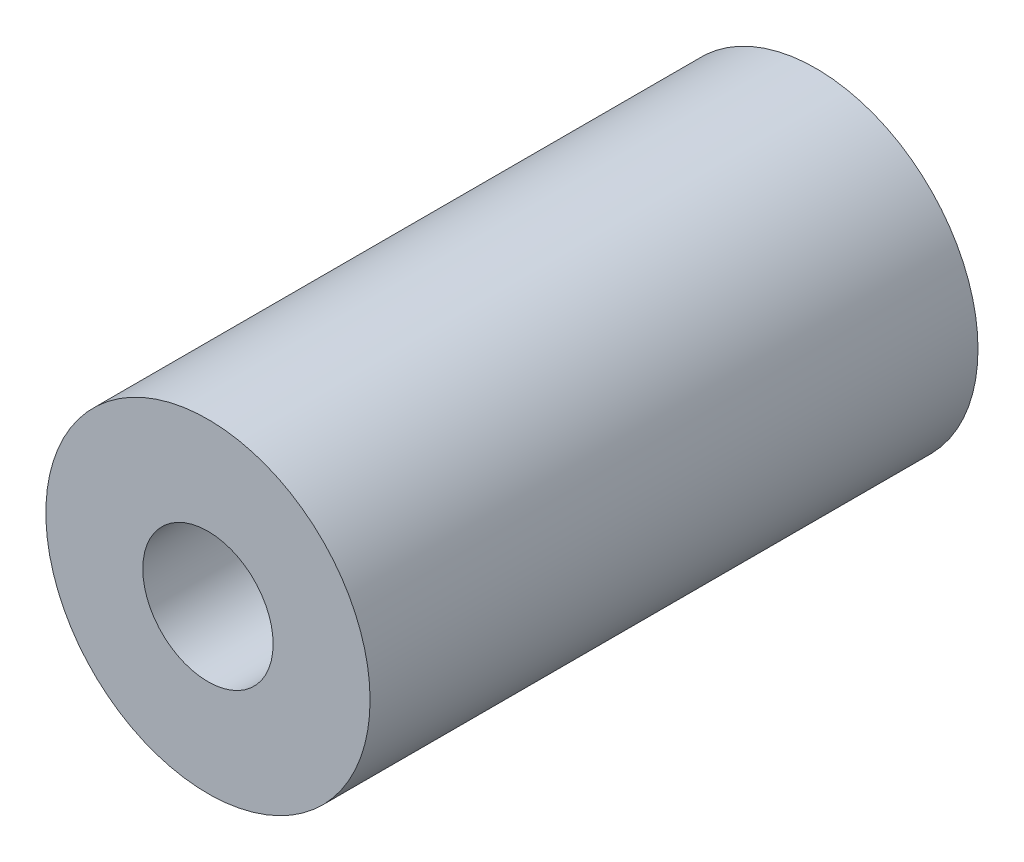
SolidWorks part; units mm, degrees
material "6061-T6 (SS)"
ref_plane "Front Plane" through (0, 0, 0) normal (0, 0, 1) x (1, 0, 0)
ref_plane "Top Plane" through (0, 0, 0) normal (0, 1, 0) x (1, 0, 0)
ref_plane "Right Plane" through (0, 0, 0) normal (1, 0, 0) x (0, 0, -1)
sketch "Sketch1" plane through (0, 0, 0) normal (0, 0, 1) x (1, 0, 0)
  circle A0 centre (0, 0) radius 6.35
  dimension "D1" = 12.7
extrude "Boss-Extrude1" add sketch "Sketch1" along normal mid plane 23.8125
hole_wizard "1/4-20 Tapped Hole1" positions "3DSketch1" profile "Sketch2" tap size "1/4-20" standard "ANSI Inch"
sketch3d "3DSketch1"
  line L0 (0, 0, 11.9062) -> (0, 0, -11.9062) construction
  point P0 (0, 0, 11.9062)
  point P4 (0, 0, -11.9062)
sketch "Sketch2" plane through (0, 0, 11.9062) normal (1, 0, 0) x (0, -1, 0)
  line L0 (0, 0) -> (0, 18.0438)
  line L1 (0, 18.0438) -> (2.5527, 16.51)
  line L2 (2.5527, 16.51) -> (2.5527, 0)
  line L5 (2.5527, 0) -> (0, 0)
  line L10 (0, 18.0438) -> (-2.5527, 16.51) construction
  line L11 (0, -6.35) -> (0, 107.95) construction
  dimension "Tap Drill Dia." = 5.1054
  dimension "Tap Drill Depth" = 16.51
  dimension "Drill Angle" = 118
cosmetic thread "Hole Thread1" parameters "D1"=12.7, "D2"=6.35
cosmetic thread "Hole Thread2" parameters "D1"=12.7, "D2"=6.35
